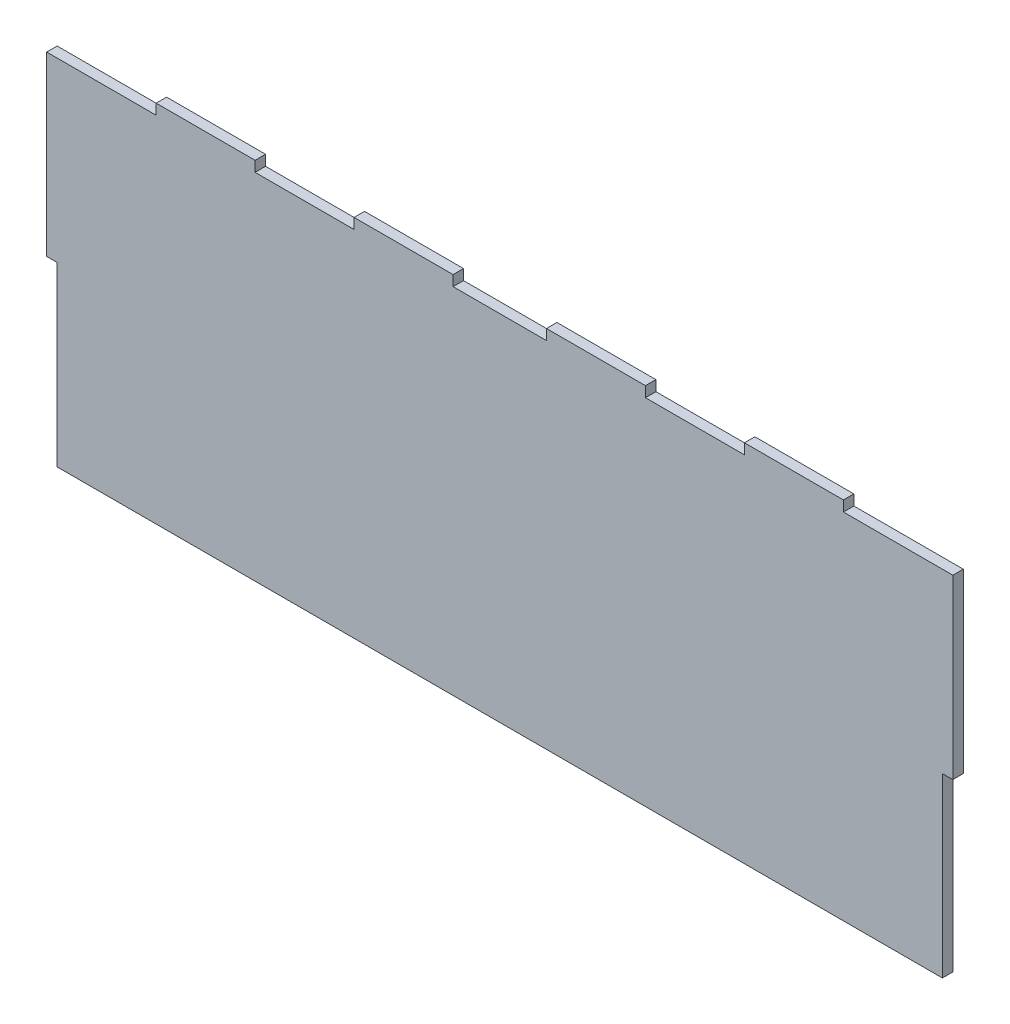
SolidWorks part; units mm, degrees
ref_plane "Alzado" through (0, 0, 0) normal (0, 0, 1) x (1, 0, 0)
ref_plane "Planta" through (0, 0, 0) normal (0, 1, 0) x (1, 0, 0)
ref_plane "Vista lateral" through (0, 0, 0) normal (1, 0, 0) x (0, 0, -1)
sketch "Croquis1" plane through (0, 0, 0) normal (0, 0, 1) x (1, 0, 0)
  line L0 (0, 101.6) -> (0, 50.8)
  line L1 (0, 101.6) -> (3, 101.6)
  line L2 (3, 101.6) -> (31.4, 101.6)
  line L3 (31.4, 101.6) -> (31.4, 104.6)
  line L4 (31.4, 104.6) -> (59.8, 104.6)
  line L5 (59.8, 104.6) -> (59.8, 101.6)
  line L6 (59.8, 101.6) -> (88.2, 101.6)
  line L7 (88.2, 101.6) -> (88.2, 104.6)
  line L8 (88.2, 104.6) -> (116.6, 104.6)
  line L9 (116.6, 104.6) -> (116.6, 101.6)
  line L10 (0, 50.8) -> (3, 50.8)
  line L11 (3, 50.8) -> (3, 0)
  line L12 (0, 0) -> (260, 0) construction
  line L13 (130, 0) -> (130, 33.8732) construction
  line L14 (257, 50.8) -> (257, 0)
  line L15 (260, 50.8) -> (257, 50.8)
  line L16 (143.4, 104.6) -> (143.4, 101.6)
  line L17 (171.8, 104.6) -> (143.4, 104.6)
  line L18 (171.8, 101.6) -> (171.8, 104.6)
  line L19 (200.2, 101.6) -> (171.8, 101.6)
  line L20 (200.2, 104.6) -> (200.2, 101.6)
  line L21 (228.6, 104.6) -> (200.2, 104.6)
  line L22 (228.6, 101.6) -> (228.6, 104.6)
  line L23 (257, 101.6) -> (228.6, 101.6)
  line L24 (260, 101.6) -> (257, 101.6)
  line L25 (260, 101.6) -> (260, 50.8)
  line L26 (116.6, 101.6) -> (143.4, 101.6)
  line L27 (3, 0) -> (257, 0)
  point P31 (260, 76.2)
  dimension "D1" = 3
  dimension "D2" = 50.8
  dimension "D3" = 50.8
  dimension "D4" = 28.4
  dimension "D5" = 3
  dimension "D6" = 260
  dimension "D7" = 3
extrude "Saliente-Extruir1" add sketch "Croquis1" along normal blind 3
